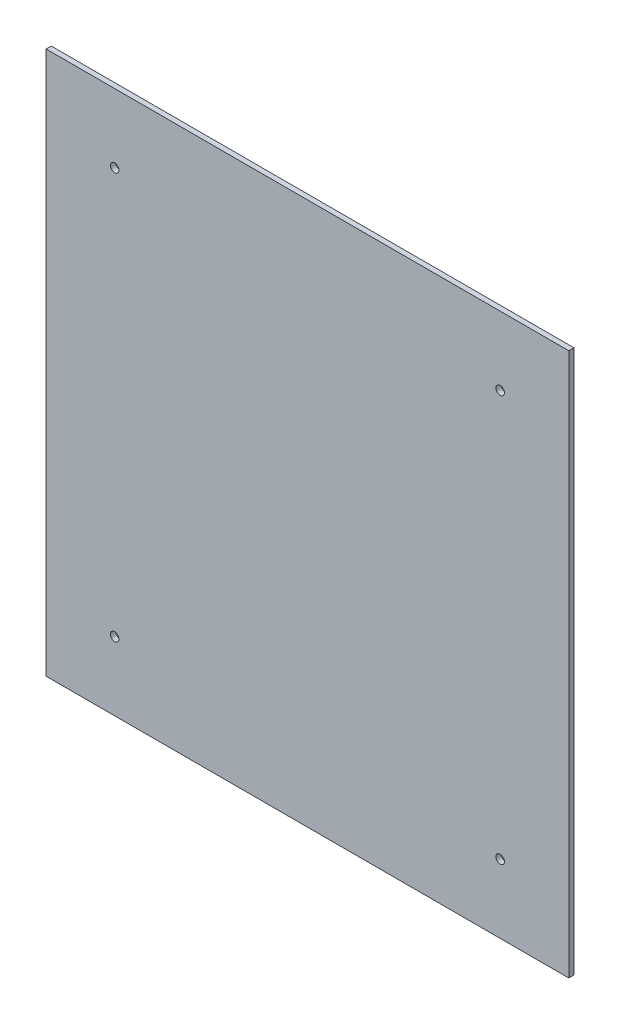
SolidWorks part; units mm, degrees
material "Copper"
ref_plane "Front Plane" through (0, 0, 0) normal (0, 0, 1) x (1, 0, 0)
ref_plane "Top Plane" through (0, 0, 0) normal (0, 1, 0) x (1, 0, 0)
ref_plane "Right Plane" through (0, 0, 0) normal (1, 0, 0) x (0, 0, -1)
sketch "Sketch1" plane through (0, 0, 0) normal (0, 0, 1) x (1, 0, 0)
  line L1 (152.4, -158.4) -> (-152.4, -158.4)
  line L2 (152.4, -158.4) -> (152.4, 158.4)
  line L3 (152.4, 158.4) -> (-152.4, 158.4)
  line L4 (-152.4, -158.4) -> (-152.4, 158.4)
  line L5 (152.4, -158.4) -> (-152.4, 158.4) construction
  line L6 (152.4, 158.4) -> (-152.4, -158.4) construction
  point P0 (0, 0)
  dimension "D1" = 316.8
  dimension "D2" = 304.8
extrude "Boss-Extrude1" add sketch "Sketch1" along normal blind 3
sketch "Sketch2" plane through (0, 0, 0) normal (0, 0, -1) x (-1, 0, 0)
  line L0 (-152.4, 158.4) -> (152.4, 158.4) construction
  line L1 (-152.4, -158.4) -> (-152.4, 158.4) construction
  line L3 (152.4, -158.4) -> (-152.4, -158.4) construction
  line L4 (152.4, 158.4) -> (152.4, -158.4) construction
  circle A4 centre (-112.4, 118.4) radius 2.5
  circle A5 centre (112.4, 118.4) radius 2.5
  circle A6 centre (112.4, -118.4) radius 2.5
  circle A7 centre (-112.4, -118.4) radius 2.5
  dimension "D2" = 40
  dimension "D9" = 5
  dimension "D10" = 5
  dimension "D11" = 5
  dimension "D12" = 5
  dimension "D3" = 40
  dimension "D4" = 40
  dimension "D5" = 40
extrude "Cut-Extrude1" cut sketch "Sketch2" against normal through all
